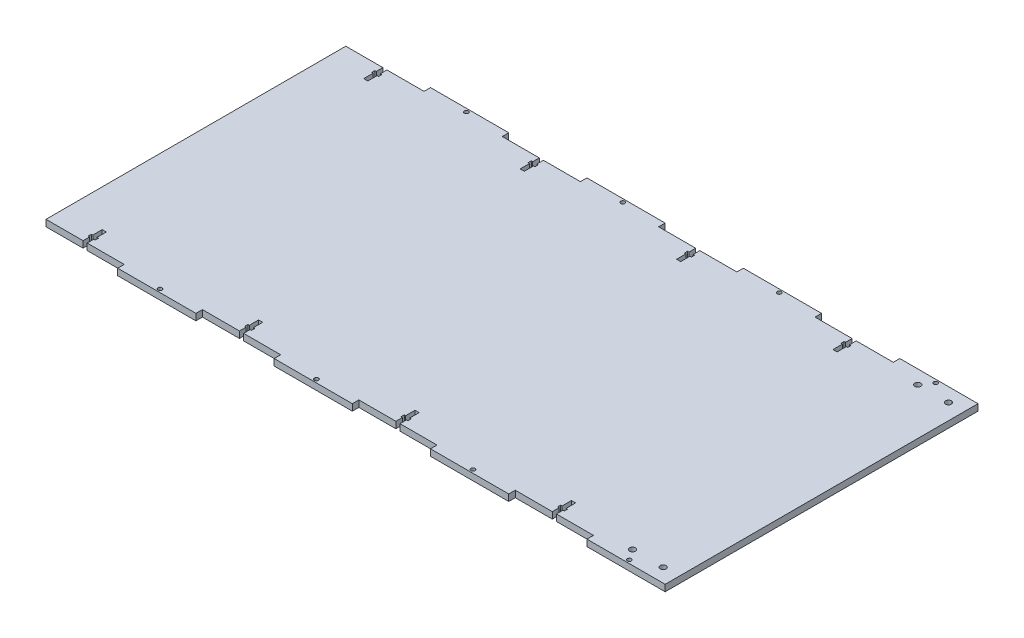
SolidWorks part; units mm, degrees
material "Acrylic (Medium-high impact)"
ref_plane "Front Plane" through (0, 0, 0) normal (0, 0, 1) x (1, 0, 0)
ref_plane "Top Plane" through (0, 0, 0) normal (0, 1, 0) x (1, 0, 0)
ref_plane "Right Plane" through (0, 0, 0) normal (1, 0, 0) x (0, 0, -1)
sketch "Sketch1" plane through (0, 0, 0) normal (0, 1, 0) x (1, 0, 0)
  line L0 (304.8, 0) -> (-304.8, 0)
  line L1 (-304.8, -152.4) -> (304.8, -152.4)
  line L2 (-304.8, -152.4) -> (-304.8, 152.4)
  line L3 (-304.8, 152.4) -> (304.8, 152.4)
  line L4 (304.8, -152.4) -> (304.8, 152.4)
  line L5 (-304.8, -152.4) -> (304.8, 152.4) construction
  line L6 (-304.8, 152.4) -> (304.8, -152.4) construction
  point P0 (0, 0)
  dimension "D1" = 609.6
  dimension "D2" = 304.8
extrude "Boss-Extrude1" add sketch "Sketch1" along normal mid plane 6.35 contours L1 L4 L0 L2
sketch "Sketch2" plane through (0, -3.175, 0) normal (0, 1, 0) x (1, 0, 0)
  line L0 (304.8, -152.4) -> (304.8, 0) construction
  line L1 (-304.8, -152.4) -> (304.8, -152.4) construction
  line L2 (34.71, -139.65) -> (36.1, -139.65)
  line L12 (34.71, -136.45) -> (34.71, -139.65)
  line L13 (-304.8, -152.4) -> (-228.6, -152.4)
  line L14 (-304.8, -152.4) -> (-304.8, -146.05)
  line L15 (-304.8, -146.05) -> (-228.6, -146.05)
  line L16 (-228.6, -152.4) -> (-228.6, -146.05)
  line L17 (-152.4, -152.4) -> (-76.2, -152.4)
  line L18 (-152.4, -152.4) -> (-152.4, -146.05)
  line L19 (-152.4, -146.05) -> (-76.2, -146.05)
  line L20 (-76.2, -152.4) -> (-76.2, -146.05)
  line L29 (0, -152.4) -> (76.2, -152.4)
  line L30 (0, -152.4) -> (0, -146.05)
  line L31 (0, -146.05) -> (76.2, -146.05)
  line L32 (76.2, -152.4) -> (76.2, -146.05)
  line L33 (36.1, -136.45) -> (34.71, -136.45)
  line L34 (152.4, -152.4) -> (228.6, -152.4)
  line L35 (152.4, -152.4) -> (152.4, -146.05)
  line L36 (152.4, -146.05) -> (228.6, -146.05)
  line L37 (228.6, -152.4) -> (228.6, -146.05)
  line L59 (36.1, -127.4) -> (36.1, -136.45)
  line L60 (40.1, -127.4) -> (36.1, -127.4)
  line L61 (40.1, -136.45) -> (40.1, -127.4)
  line L62 (41.49, -136.45) -> (40.1, -136.45)
  line L63 (41.49, -139.65) -> (41.49, -136.45)
  line L64 (40.1, -139.65) -> (41.49, -139.65)
  line L65 (40.1, -146.05) -> (40.1, -139.65)
  line L66 (36.1, -139.65) -> (36.1, -146.05)
  line L67 (38.1, -127.4) -> (38.1, -145.9334) construction
  line L68 (-117.69, -139.65) -> (-116.3, -139.65)
  line L69 (-117.69, -136.45) -> (-117.69, -139.65)
  line L70 (-116.3, -136.45) -> (-117.69, -136.45)
  line L71 (-116.3, -127.4) -> (-116.3, -136.45)
  line L72 (-112.3, -127.4) -> (-116.3, -127.4)
  line L73 (-112.3, -136.45) -> (-112.3, -127.4)
  line L74 (-110.91, -136.45) -> (-112.3, -136.45)
  line L75 (-110.91, -139.65) -> (-110.91, -136.45)
  line L76 (-112.3, -139.65) -> (-110.91, -139.65)
  line L77 (-112.3, -146.05) -> (-112.3, -139.65)
  line L78 (-116.3, -139.65) -> (-116.3, -146.05)
  line L79 (-114.3, -127.4) -> (-114.3, -145.9334) construction
  line L80 (-270.09, -139.65) -> (-268.7, -139.65)
  line L81 (-270.09, -136.45) -> (-270.09, -139.65)
  line L82 (-268.7, -136.45) -> (-270.09, -136.45)
  line L83 (-268.7, -127.4) -> (-268.7, -136.45)
  line L84 (-264.7, -127.4) -> (-268.7, -127.4)
  line L85 (-264.7, -136.45) -> (-264.7, -127.4)
  line L86 (-263.31, -136.45) -> (-264.7, -136.45)
  line L87 (-263.31, -139.65) -> (-263.31, -136.45)
  line L88 (-264.7, -139.65) -> (-263.31, -139.65)
  line L89 (-264.7, -146.05) -> (-264.7, -139.65)
  line L90 (-268.7, -139.65) -> (-268.7, -146.05)
  line L91 (-266.7, -127.4) -> (-266.7, -145.9334) construction
  line L107 (228.6, -146.05) -> (304.8, -146.05) construction
  line L108 (190.5, -127.4) -> (190.5, -145.9334) construction
  line L109 (188.5, -139.65) -> (188.5, -146.05)
  line L110 (187.11, -139.65) -> (188.5, -139.65)
  line L111 (187.11, -136.45) -> (187.11, -139.65)
  line L112 (188.5, -136.45) -> (187.11, -136.45)
  line L113 (188.5, -127.4) -> (188.5, -136.45)
  line L114 (192.5, -127.4) -> (188.5, -127.4)
  line L115 (192.5, -136.45) -> (192.5, -127.4)
  line L116 (193.89, -136.45) -> (192.5, -136.45)
  line L117 (193.89, -139.65) -> (193.89, -136.45)
  line L118 (192.5, -139.65) -> (193.89, -139.65)
  line L119 (192.5, -146.05) -> (192.5, -139.65)
  circle A0 centre (289.39, -139) radius 2.875
  circle A3 centre (259.53, -139) radius 2.875
  circle A8 centre (266.7, -149.225) radius 2
  circle A9 centre (114.3, -149.225) radius 2
  circle A10 centre (-38.1, -149.225) radius 2
  circle A11 centre (-190.5, -149.225) radius 2
  point P34 (190.5, -127.4)
  dimension "D11" = 6.35
  dimension "D12" = 76.2
  dimension "D13" = 5.75
  dimension "D14" = 5.75
  dimension "D19" = 3.2
  dimension "D20" = 6.4
  dimension "D10" = 4
  dimension "D1" = 6.35
  dimension "D2" = 76.2
  dimension "D3" = 76.2
  dimension "D4" = 76.2
  dimension "D5" = 76.2
  dimension "D6" = 76.2
  dimension "D7" = 76.2
  dimension "D8" = 76.2
  dimension "D9" = 7.05
  dimension "D15" = 4
  dimension "D16" = 29.86
  dimension "D17" = 6.78
  dimension "D18" = 15.41
  dimension "D21" = 38.1
  dimension "D22" = 18.65
  dimension "D23" = 3.175
  dimension "D24" = 38.1
extrude "Cut-Extrude1" cut sketch "Sketch2" along direction (0, 1, 0) on the side of the normal through all
mirror "Mirror1" about plane through (0, 3.175, 0) normal (0, 0, 1) of "Cut-Extrude1", "Boss-Extrude1"
